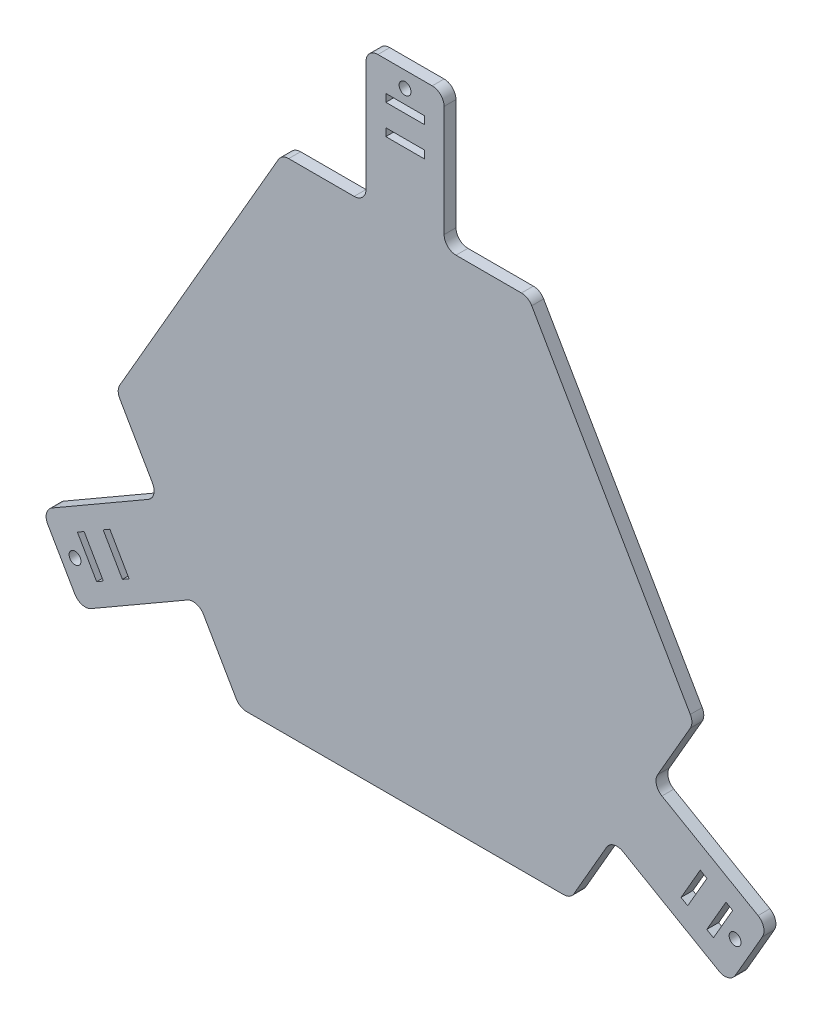
SolidWorks part; units mm, degrees
ref_plane "Спереди" through (0, 0, 0) normal (0, 0, 1) x (1, 0, 0)
ref_plane "Сверху" through (0, 0, 0) normal (0, 1, 0) x (1, 0, 0)
ref_plane "Справа" through (0, 0, 0) normal (1, 0, 0) x (0, 0, -1)
other "Configuration Table"
sketch "Эскиз1" plane through (0, 0, 0) normal (0, 0, 1) x (1, 0, 0)
  line L0 (0, 0) -> (-158.7702, -91.666) construction
  line L4 (-77.8045, -50.5207) -> (-82.6545, -42.1203)
  line L6 (-88.8379, -46.4103) -> (-84.6114, -53.7308)
  line L12 (82.6545, -42.1203) -> (76.1157, -49.5457) construction
  line L13 (-77.8045, -50.5207) -> (-76.1157, -49.5457)
  line L14 (-82.6545, -42.1203) -> (-80.9657, -41.1453)
  line L15 (-76.1157, -49.5457) -> (-80.9657, -41.1453)
  line L16 (-77.8045, -50.5207) -> (-80.9657, -41.1453) construction
  line L17 (-82.6545, -42.1203) -> (-76.1157, -49.5457) construction
  line L26 (-71.3093, -46.7707) -> (-76.1593, -38.3703)
  line L27 (-71.3093, -46.7707) -> (-69.6205, -45.7957)
  line L28 (-76.1593, -38.3703) -> (-74.4705, -37.3953)
  line L29 (-69.6205, -45.7957) -> (-74.4705, -37.3953)
  line L39 (-88.8379, -46.4103) -> (-90.1497, -44.1382)
  line L40 (-89.0516, -40.0402) -> (-64.8029, -26.0402)
  line L41 (-63.7048, -21.9421) -> (-71.9615, -7.641)
  line L43 (-79.2016, -57.1009) -> (-54.9529, -43.1009)
  line L44 (-84.6114, -53.7308) -> (-83.2997, -56.0028)
  line L45 (-50.8548, -44.1989) -> (-42.5981, -58.5)
  line L46 (0, 0) -> (0, 96.141) construction
  line L48 (77.8045, -50.5207) -> (80.9657, -41.1453) construction
  line L49 (50.8548, -44.1989) -> (42.5981, -58.5)
  line L50 (84.6114, -53.7308) -> (83.2997, -56.0028)
  line L51 (79.2016, -57.1009) -> (54.9529, -43.1009)
  line L52 (63.7048, -21.9421) -> (71.9615, -7.641)
  line L53 (89.0516, -40.0402) -> (64.8029, -26.0402)
  line L54 (88.8379, -46.4103) -> (90.1497, -44.1382)
  line L55 (69.6205, -45.7957) -> (74.4705, -37.3953)
  line L56 (76.1593, -38.3703) -> (74.4705, -37.3953)
  line L57 (71.3093, -46.7707) -> (69.6205, -45.7957)
  line L58 (71.3093, -46.7707) -> (76.1593, -38.3703)
  line L59 (76.1157, -49.5457) -> (80.9657, -41.1453)
  line L60 (82.6545, -42.1203) -> (80.9657, -41.1453)
  line L61 (77.8045, -50.5207) -> (76.1157, -49.5457)
  line L62 (88.8379, -46.4103) -> (84.6114, -53.7308)
  line L63 (77.8045, -50.5207) -> (82.6545, -42.1203)
  line L64 (-40, -60) -> (40, -60)
  line L66 (0, 0) -> (86.7247, -50.0705) construction
  line L67 (-4.85, 92.641) -> (4.85, 90.691) construction
  line L68 (4.85, 92.641) -> (-4.85, 90.691) construction
  line L69 (-4.85, 92.641) -> (4.85, 92.641)
  line L70 (4.2265, 100.141) -> (-4.2265, 100.141)
  line L71 (-4.85, 92.641) -> (-4.85, 90.691)
  line L72 (4.85, 92.641) -> (4.85, 90.691)
  line L73 (-4.85, 90.691) -> (4.85, 90.691)
  line L74 (-4.85, 85.141) -> (4.85, 85.141)
  line L75 (-4.85, 85.141) -> (-4.85, 83.191)
  line L76 (4.85, 85.141) -> (4.85, 83.191)
  line L77 (-4.85, 83.191) -> (4.85, 83.191)
  line L78 (4.2265, 100.141) -> (6.85, 100.141)
  line L79 (9.85, 97.141) -> (9.85, 69.141)
  line L80 (12.85, 66.141) -> (29.3634, 66.141)
  line L81 (-9.85, 97.141) -> (-9.85, 69.141)
  line L82 (-4.2265, 100.141) -> (-6.85, 100.141)
  line L83 (-12.85, 66.141) -> (-29.3634, 66.141)
  line L84 (-71.9615, -4.641) -> (-31.9615, 64.641)
  line L85 (31.9615, 64.641) -> (71.9615, -4.641)
  arc A0 (79.2016, -57.1009) -> (83.2997, -56.0028) centre (80.7016, -54.5028) ccw
  circle A1 centre (-83.2606, -48.0705) radius 1.5
  arc A11 (-90.1497, -44.1382) -> (-89.0516, -40.0402) centre (-87.5516, -42.6382) cw
  arc A12 (-71.9615, -7.641) -> (-71.9615, -4.641) centre (-69.3634, -6.141) cw
  arc A13 (-40, -60) -> (-42.5981, -58.5) centre (-40, -57) cw
  arc A14 (-63.7048, -21.9421) -> (-64.8029, -26.0402) centre (-66.3029, -23.4421) cw
  arc A15 (-50.8548, -44.1989) -> (-54.9529, -43.1009) centre (-53.4529, -45.6989) ccw
  arc A16 (-79.2016, -57.1009) -> (-83.2997, -56.0028) centre (-80.7016, -54.5028) cw
  arc A17 (50.8548, -44.1989) -> (54.9529, -43.1009) centre (53.4529, -45.6989) cw
  arc A18 (63.7048, -21.9421) -> (64.8029, -26.0402) centre (66.3029, -23.4421) ccw
  arc A19 (40, -60) -> (42.5981, -58.5) centre (40, -57) ccw
  arc A20 (71.9615, -7.641) -> (71.9615, -4.641) centre (69.3634, -6.141) ccw
  arc A21 (90.1497, -44.1382) -> (89.0516, -40.0402) centre (87.5516, -42.6382) ccw
  circle A22 centre (83.2606, -48.0705) radius 1.5
  circle A23 centre (0, 96.141) radius 1.5
  arc A24 (6.85, 100.141) -> (9.85, 97.141) centre (6.85, 97.141) cw
  arc A25 (29.3634, 66.141) -> (31.9615, 64.641) centre (29.3634, 63.141) cw
  arc A26 (-31.9615, 64.641) -> (-29.3634, 66.141) centre (-29.3634, 63.141) cw
  arc A27 (12.85, 66.141) -> (9.85, 69.141) centre (12.85, 69.141) cw
  arc A28 (-12.85, 66.141) -> (-9.85, 69.141) centre (-12.85, 69.141) ccw
  arc A29 (-9.85, 97.141) -> (-6.85, 100.141) centre (-6.85, 97.141) cw
  circle A30 centre (0, 0) radius 60 construction
  point P4 (-79.3851, -45.833)
  point P9 (-86.7247, -50.0705)
  point P65 (-91.6497, -41.5402)
  point P68 (0, 0)
  point P71 (0, 0)
  point P74 (-62.2048, -24.5402)
  point P77 (-52.3548, -41.6009)
  point P80 (-81.7997, -58.6009)
  point P91 (81.7997, -58.6009)
  point P92 (52.3548, -41.6009)
  point P93 (62.2048, -24.5402)
  point P94 (0, 0)
  point P95 (0, 0)
  point P96 (91.6497, -41.5402)
  point P99 (86.7247, -50.0705)
  point P100 (79.3851, -45.833)
  point P114 (0, 91.666)
  point P115 (0, 100.141)
  point P118 (9.85, 100.141)
  point P119 (0, 0)
  point P120 (0, 0)
  point P121 (9.85, 66.141)
  point P122 (-9.85, 66.141)
  point P123 (-9.85, 100.141)
  dimension "D5" = 3
  dimension "D12" = 8.453
  dimension "D13" = 5
  dimension "D2" = 120
  dimension "D16" = 3
  dimension "D17" = 3
  dimension "D3" = 1.95
  dimension "D4" = 80
  dimension "D6" = 9.7
  dimension "D7" = 4
  dimension "D9" = 3.5
  dimension "D10" = 5.55
  dimension "D11" = 1.95
  dimension "D15" = 34
extrude "Бобышка-Вытянуть3" add sketch "Эскиз1" along normal blind 3
